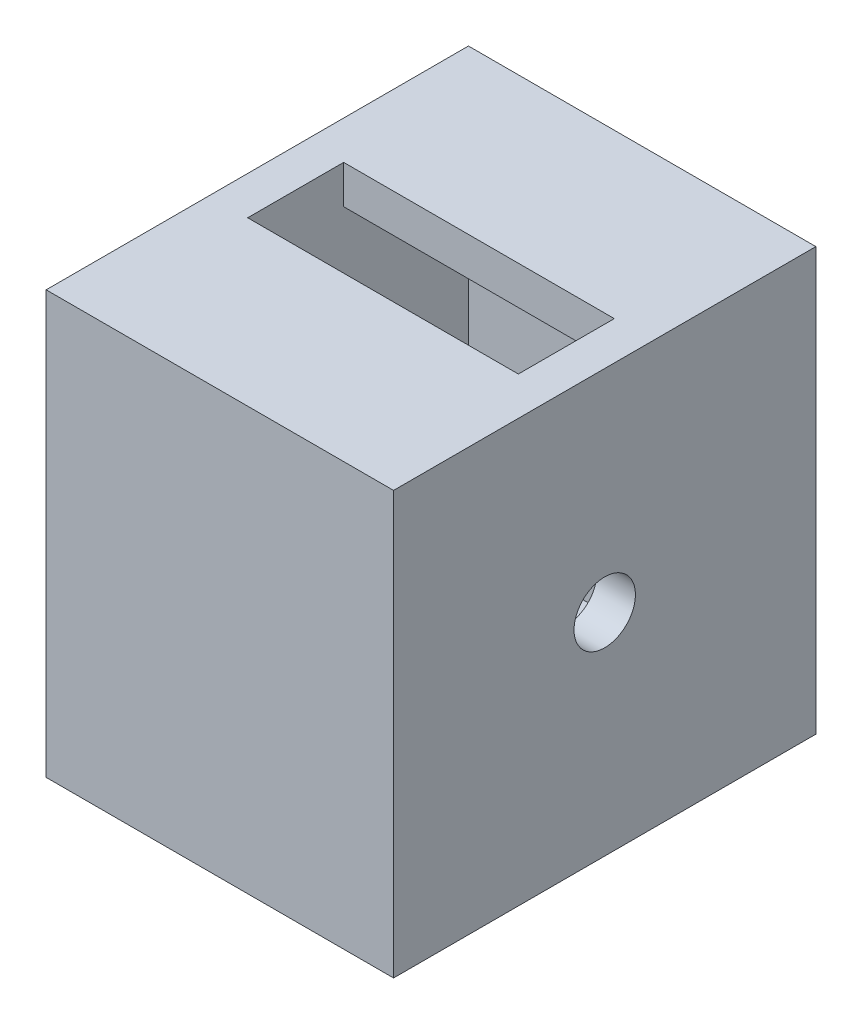
SolidWorks part; units mm, degrees
material "TPU 74D"
ref_plane "Front Plane" through (0, 0, 0) normal (0, 0, 1) x (1, 0, 0)
ref_plane "Top Plane" through (0, 0, 0) normal (0, 1, 0) x (1, 0, 0)
ref_plane "Right Plane" through (0, 0, 0) normal (1, 0, 0) x (0, 0, -1)
sketch "Sketch2" plane through (0, 0, 0) normal (0, 1, 0) x (1, 0, 0)
  line L0 (-8.9535, 11.43) -> (-8.9535, 13.97) construction
  line L1 (8.9535, 11.43) -> (-8.9535, 11.43)
  line L2 (8.9535, 11.43) -> (8.9535, -11.43)
  line L3 (8.9535, -11.43) -> (-8.9535, -11.43)
  line L4 (-8.9535, 11.43) -> (-8.9535, -11.43)
  line L5 (11.4935, 13.97) -> (-11.4935, 13.97)
  line L6 (11.4935, 13.97) -> (11.4935, -13.97)
  line L7 (11.4935, -13.97) -> (-11.4935, -13.97)
  line L8 (-11.4935, 13.97) -> (-11.4935, -13.97)
  line L9 (-8.9535, 11.43) -> (-11.4935, 11.43) construction
  point P8 (0, 13.97)
  point P9 (0, 11.43)
  point P11 (-8.9535, 0)
  point P12 (-11.4935, 0)
  dimension "D1" = 17.907
  dimension "D2" = 22.86
  dimension "D3" = 2.54
extrude "Boss-Extrude1" add sketch "Sketch2" along normal mid plane 27.94
sketch "Sketch3" plane through (0, -13.97, 0) normal (0, -1, 0) x (1, 0, 0)
  line L1 (-8.9535, 11.43) -> (8.9535, 11.43)
  line L2 (-8.9535, 11.43) -> (-8.9535, -11.43)
  line L3 (-8.9535, -11.43) -> (8.9535, -11.43)
  line L4 (8.9535, 11.43) -> (8.9535, -11.43)
extrude "Boss-Extrude2" add sketch "Sketch3" against normal blind 2.54
sketch "Sketch4" plane through (0, 13.97, 0) normal (0, 1, 0) x (1, 0, 0)
  line L0 (8.9535, -11.43) -> (8.9535, 11.43) construction
  line L1 (-8.9535, 11.43) -> (8.9535, 11.43)
  line L2 (-8.9535, 11.43) -> (-8.9535, 3.175)
  line L3 (-8.9535, 3.175) -> (8.9535, 3.175)
  line L4 (8.9535, 11.43) -> (8.9535, 3.175)
  line L11 (-8.9535, -11.43) -> (8.9535, -11.43) construction
  line L12 (-8.9535, -11.43) -> (8.9535, -11.43)
  line L13 (-8.9535, -11.43) -> (-8.9535, -3.175)
  line L14 (-8.9535, -3.175) -> (8.9535, -3.175)
  line L15 (8.9535, -11.43) -> (8.9535, -3.175)
  line L16 (8.9535, -11.43) -> (-8.9535, -11.43) construction
  dimension "D1" = 6.35
extrude "Boss-Extrude3" add sketch "Sketch4" against normal blind 2.54
sketch "Sketch5" plane through (-11.4935, 0, 0) normal (-1, 0, 0) x (0, 0, 1)
  line L1 (-13.97, -13.97) -> (13.97, -13.97)
  line L2 (-13.97, -13.97) -> (-13.97, 13.97)
  line L3 (-13.97, 13.97) -> (13.97, 13.97)
  line L4 (13.97, -13.97) -> (13.97, 13.97)
  line L5 (-13.97, -13.97) -> (13.97, 13.97) construction
  line L6 (-13.97, 13.97) -> (13.97, -13.97) construction
  circle A0 centre (0, 0) radius 10.033
  point P0 (0, 0)
  dimension "D1" = 20.066
extrude "Cut-Extrude1" [suppressed] cut sketch "Sketch5" against normal up to surface (2.54 mm away) contours A0
sketch "Sketch6" plane through (11.4935, 0, 0) normal (1, 0, 0) x (0, 0, -1)
  line L1 (-13.97, -13.97) -> (13.97, -13.97)
  line L2 (-13.97, -13.97) -> (-13.97, 13.97)
  line L3 (-13.97, 13.97) -> (13.97, 13.97)
  line L4 (13.97, -13.97) -> (13.97, 13.97)
  line L5 (-13.97, -13.97) -> (13.97, 13.97) construction
  line L6 (-13.97, 13.97) -> (13.97, -13.97) construction
  circle A0 centre (0, 0) radius 2.032
  point P0 (0, 0)
  dimension "D1" = 4.064
extrude "Cut-Extrude2" cut sketch "Sketch6" against normal up to surface (2.54 mm away) contours A0 up to face at (8.9535, 6.35, 0)
sketch "Sketch7" plane through (0, 0, -13.97) normal (0, 0, -1) x (-1, 0, 0)
  line L0 (-11.4935, 13.97) -> (-11.4935, -13.97) construction
  line L1 (-5.7785, -3.175) -> (-2.6035, -3.175)
  line L2 (-5.7785, -3.175) -> (-5.7785, 3.175)
  line L3 (-5.7785, 3.175) -> (-2.6035, 3.175)
  line L4 (-2.6035, -3.175) -> (-2.6035, 3.175)
  line L5 (-5.7785, -3.175) -> (-2.6035, 3.175) construction
  line L6 (-5.7785, 3.175) -> (-2.6035, -3.175) construction
  point P0 (-4.191, 0)
  dimension "D1" = 3.175
  dimension "D2" = 5.715
  dimension "D3" = 6.35
extrude "Cut-Extrude3" cut sketch "Sketch7" against normal up to surface (2.54 mm away) contours L4 L3 L2 L1 up to face at (0, 0, -11.43)
sketch "Sketch10" [suppressed] plane through (0, 0, 13.97) normal (0, 0, 1) x (1, 0, 0)
  line L0 (10.16, 13.97) -> (10.16, -13.97) construction
  line L1 (1.27, -3.175) -> (4.445, -3.175)
  line L2 (1.27, -3.175) -> (1.27, 3.175)
  line L3 (1.27, 3.175) -> (4.445, 3.175)
  line L4 (4.445, -3.175) -> (4.445, 3.175)
  line L5 (1.27, -3.175) -> (4.445, 3.175) construction
  line L6 (1.27, 3.175) -> (4.445, -3.175) construction
  point P0 (2.8575, 0)
  dimension "D1" = 5.715
  dimension "D2" = 3.175
  dimension "D3" = 6.35
extrude "Cut-Extrude4" [suppressed] cut sketch "Sketch10" against normal up to next
fillet "Fillet1" [suppressed] radius 2.54
fillet "Fillet2" [suppressed] radius 1.2446
